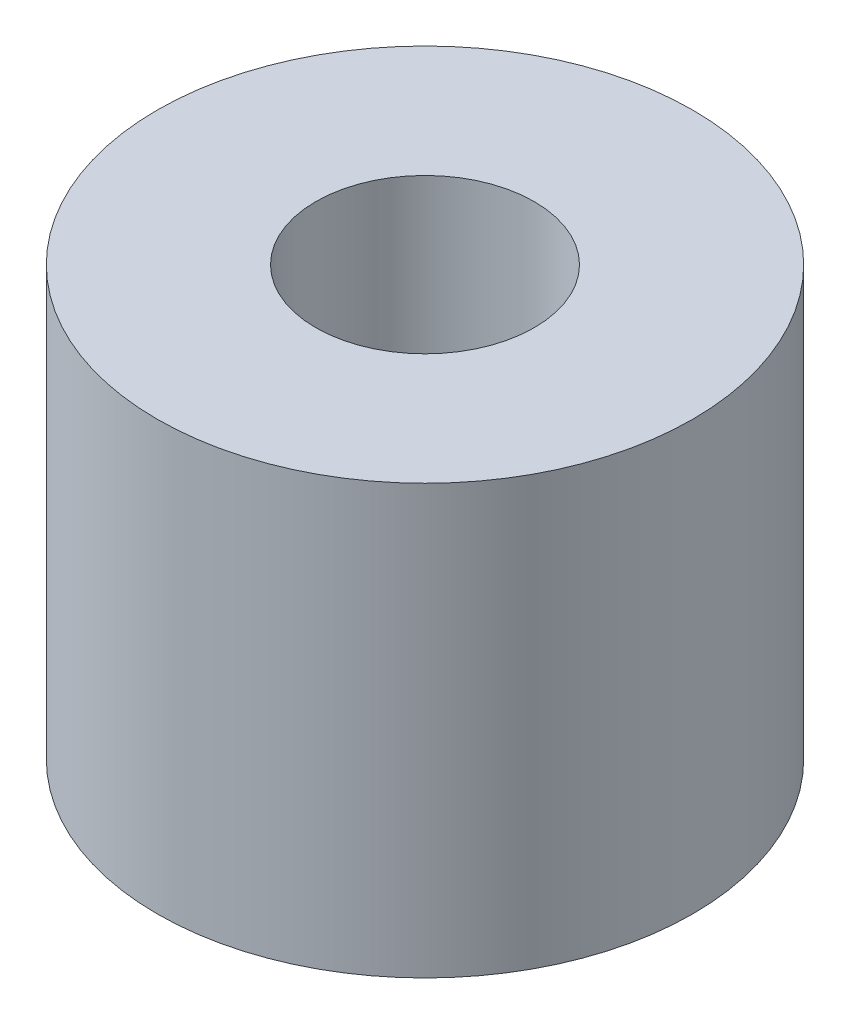
SolidWorks part; units mm, degrees
ref_plane "Спереди" through (0, 0, 0) normal (0, 0, 1) x (1, 0, 0)
ref_plane "Сверху" through (0, 0, 0) normal (0, 1, 0) x (1, 0, 0)
ref_plane "Справа" through (0, 0, 0) normal (1, 0, 0) x (0, 0, -1)
sketch "Эскиз1" plane through (0, 0, 0) normal (0, 0, 1) x (1, 0, 0)
  line L0 (0, 0) -> (0, -43.731) construction
  line L1 (0, 0) -> (-5.1, 0) construction
  line L3 (-5.1, 0) -> (-12.5, 0)
  line L4 (-5.1, 0) -> (-5.1, 20)
  line L5 (-5.1, 20) -> (-12.5, 20)
  line L6 (-12.5, 0) -> (-12.5, 20)
  dimension "D1" = 10.2
  dimension "D2" = 25
  dimension "D3" = 20
revolve "Повернуть1" add sketch "Эскиз1" angle 360 about L0
